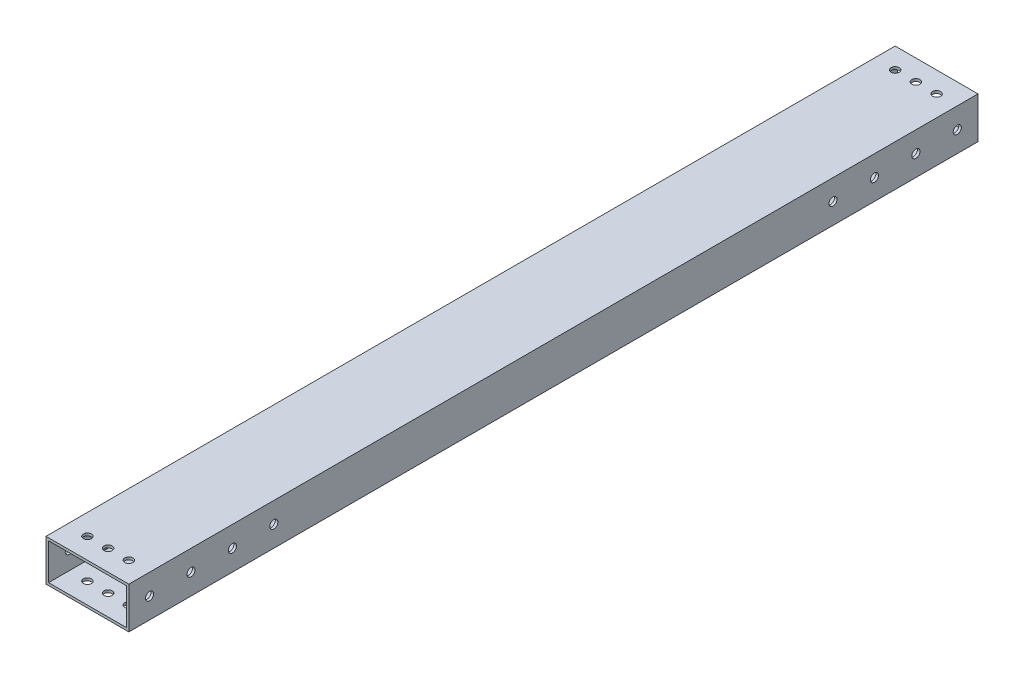
SolidWorks part; units mm, degrees
material "6061-T6 (SS)"
ref_plane "Front Plane" through (0, 0, 0) normal (0, 0, 1) x (1, 0, 0)
ref_plane "Top Plane" through (0, 0, 0) normal (0, 1, 0) x (1, 0, 0)
ref_plane "Right Plane" through (0, 0, 0) normal (1, 0, 0) x (0, 0, -1)
sketch "Sketch1" plane through (0, 0, 0) normal (0, 0, 1) x (1, 0, 0)
  line L0 (-23.8125, 11.1125) -> (23.8125, 11.1125)
  line L1 (-25.4, -12.7) -> (25.4, -12.7)
  line L2 (-25.4, -12.7) -> (-25.4, 12.7)
  line L3 (-25.4, 12.7) -> (25.4, 12.7)
  line L4 (25.4, -12.7) -> (25.4, 12.7)
  line L5 (-25.4, -12.7) -> (25.4, 12.7) construction
  line L6 (-25.4, 12.7) -> (25.4, -12.7) construction
  line L7 (23.8125, -11.1125) -> (23.8125, 11.1125)
  line L8 (-23.8125, -11.1125) -> (23.8125, -11.1125)
  line L9 (-23.8125, -11.1125) -> (-23.8125, 11.1125)
  point P0 (0, 0)
  dimension "D1" = 50.8
  dimension "D2" = 25.4
  dimension "D3" = 1.5875
extrude "Boss-Extrude1" add sketch "Sketch1" along normal mid plane 520.7
sketch "Sketch2" plane through (0, 12.7, 0) normal (0, 1, 0) x (1, 0, 0)
  line L0 (25.4, 260.35) -> (-25.4, 260.35) construction
  line L1 (-25.4, 0) -> (25.4, 0) construction
  line L2 (-25.4, -260.35) -> (-25.4, 260.35) construction
  line L3 (25.4, -260.35) -> (25.4, 260.35) construction
  circle A0 centre (-12.7, 247.65) radius 2.4892
  circle A1 centre (0, 247.65) radius 2.4892
  circle A2 centre (12.7, 247.65) radius 2.4892
  circle A3 centre (12.7, -247.65) radius 2.4892
  circle A4 centre (0, -247.65) radius 2.4892
  circle A5 centre (-12.7, -247.65) radius 2.4892
  point P9 (0, 260.35)
  dimension "D1" = 4.9784
  dimension "D2" = 12.7
  dimension "D3" = 12.7
  dimension "D4" = 12.7
extrude "Cut-Extrude1" cut sketch "Sketch2" against normal through all
sketch "Sketch3" plane through (25.4, 0, 0) normal (1, 0, 0) x (0, 0, -1)
  line L0 (260.35, -12.7) -> (260.35, 12.7) construction
  line L1 (0, 12.7) -> (0, -12.7) construction
  line L2 (-260.35, 12.7) -> (260.35, 12.7) construction
  line L3 (-260.35, -12.7) -> (260.35, -12.7) construction
  circle A0 centre (247.65, 0) radius 2.4892
  circle A1 centre (-247.65, 0) radius 2.4892
  circle A2 centre (222.25, 0) radius 2.4892
  circle A3 centre (196.85, 0) radius 2.4892
  circle A4 centre (171.45, 0) radius 2.4892
  circle A7 centre (-171.45, 0) radius 2.4892
  circle A8 centre (-196.85, 0) radius 2.4892
  circle A9 centre (-222.25, 0) radius 2.4892
  point P5 (260.35, 0)
  dimension "D1" = 12.7
  dimension "D2" = 4.9784
  dimension "D4" = 25.4
  dimension "D3" = 4
extrude "Cut-Extrude2" cut sketch "Sketch3" against normal through all
